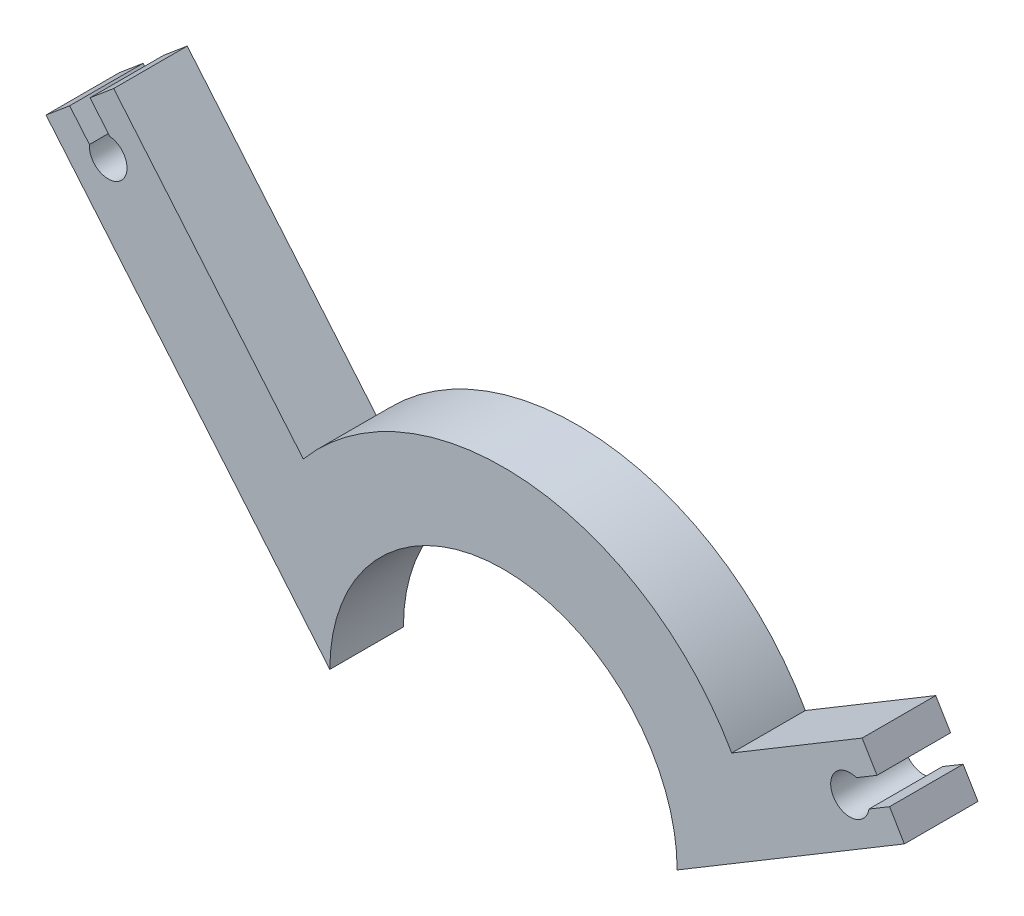
SolidWorks part; units mm, degrees
ref_plane "Front Plane" through (0, 0, 0) normal (0, 0, 1) x (1, 0, 0)
ref_plane "Top Plane" through (0, 0, 0) normal (0, 1, 0) x (1, 0, 0)
ref_plane "Right Plane" through (0, 0, 0) normal (1, 0, 0) x (0, 0, -1)
sketch "Sketch2" plane through (0, 0, 0) normal (0, 0, 1) x (1, 0, 0)
  line L0 (-3.7465, 0) -> (-9.8691, 7.2966)
  line L1 (3.7465, 0) -> (8.6488, 2.9375)
  line L2 (8.6488, 2.9375) -> (8.3278, 3.4731)
  line L3 (7.7367, 4.4597) -> (4.9238, 2.7741)
  line L4 (-9.8691, 7.2966) -> (-9.3595, 7.7241)
  line L5 (-8.4097, 8.5211) -> (-4.3186, 3.6454)
  line L6 (-7.078, 5.4522) -> (-3.6242, 1.3361) construction
  line L7 (-9.3595, 7.7241) -> (-8.932, 7.2146)
  line L8 (-8.9193, 8.0935) -> (-8.4917, 7.584)
  line L9 (-8.9193, 8.0935) -> (-8.4097, 8.5211)
  line L10 (8.1927, 3.6986) -> (7.4726, 3.2671) construction
  line L11 (8.3278, 3.4731) -> (7.883, 3.2065)
  line L12 (8.0576, 3.9241) -> (7.6127, 3.6575)
  line L13 (8.0576, 3.9241) -> (7.7367, 4.4597)
  arc A0 (3.7465, 0) -> (-3.7465, 0) centre (0, 0) ccw
  arc A1 (4.9238, 2.7741) -> (-4.3186, 3.6454) centre (0, 0) ccw
  circle A2 centre (0, 0) radius 5.6515 construction
  circle A3 centre (0, 0) radius 3.7465 construction
  arc A4 (-8.932, 7.2146) -> (-8.4917, 7.584) centre (-8.5271, 7.1792) ccw
  arc A5 (7.6127, 3.6575) -> (7.883, 3.2065) centre (7.4726, 3.2671) ccw
  dimension "D1" = 7.493
  dimension "D5" = 0.8128
  dimension "D3" = 9.525
  dimension "D4" = 5.715
  dimension "D6" = 1.905
  dimension "D7" = 0.8395
  dimension "D8" = 0.8872
  dimension "D9" = 0.8872
  dimension "D2" = 1.905
extrude "Boss-Extrude1" add sketch "Sketch2" along normal blind 1.5875
equation "\"D8@Sketch2\" = \"D9@Sketch2\""
